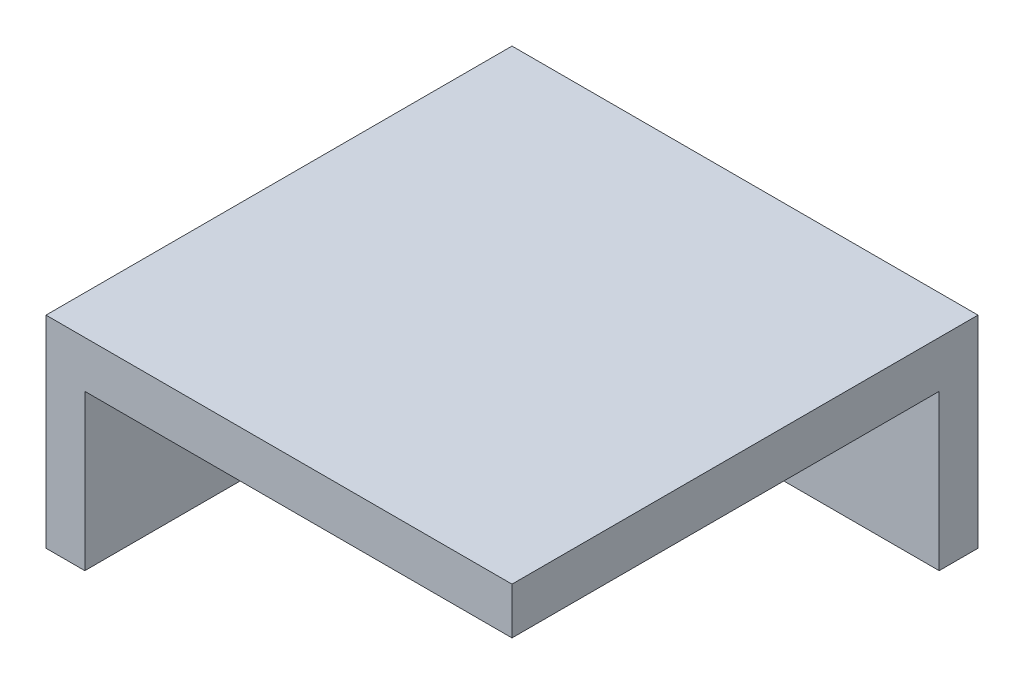
SolidWorks part; units mm, degrees
ref_plane "Front Plane" through (0, 0, 0) normal (0, 0, 1) x (1, 0, 0)
ref_plane "Top Plane" through (0, 0, 0) normal (0, 1, 0) x (1, 0, 0)
ref_plane "Right Plane" through (0, 0, 0) normal (1, 0, 0) x (0, 0, -1)
sketch "Sketch1" plane through (0, 0, 0) normal (0, 1, 0) x (1, 0, 0)
  line L1 (30, 30) -> (-30, 30)
  line L2 (-30, 30) -> (-30, -30)
  line L3 (-30, -30) -> (30, -30)
  line L4 (30, -30) -> (30, 30)
  circle A0 centre (0, 0) radius 30 construction
  dimension "D1" = 60
extrude "Boss-Extrude1" add sketch "Sketch1" along normal blind 6
sketch "Sketch2" plane through (0, 0, 0) normal (0, 1, 0) x (1, 0, 0)
  line L0 (-30, -30) -> (30, -30) construction
  line L2 (-30, 30) -> (-30, -30)
  line L3 (-30, -30) -> (-25, -30)
  line L4 (-25, 25) -> (-25, -30)
  line L5 (30, -30) -> (30, 30) construction
  line L6 (-30, 30) -> (30, 30)
  line L8 (-25, 25) -> (30, 25)
  line L9 (30, 30) -> (30, 25)
  dimension "D1" = 5
  dimension "D2" = 5
extrude "Boss-Extrude2" add sketch "Sketch2" against normal blind 20
sketch "Sketch3" plane through (0, 0, -25) normal (0, 0, 1) x (1, 0, 0)
  line L0 (-25, -20) -> (-25, 0) construction
  line L1 (-22, -7.3707) -> (-22, -1.3707)
  line L2 (-25, -1.3707) -> (-22, -1.3707)
  line L3 (-25, -7.3707) -> (-22, -7.3707)
  line L5 (-25, -12.6293) -> (-22, -12.6293)
  line L6 (-25, -10) -> (-15, -10) construction
  line L7 (-25, -18.6293) -> (-22, -18.6293)
  line L8 (-22, -12.6293) -> (-22, -18.6293)
  line L9 (-25, -20) -> (-25, 0) construction
  point P10 (-22, -15.6293)
  point P11 (-25, -14.0762)
  point P12 (0, 0)
  point P13 (0, 0)
  point P16 (-25, -14.0762)
  dimension "D1" = 3
  dimension "D2" = 6
